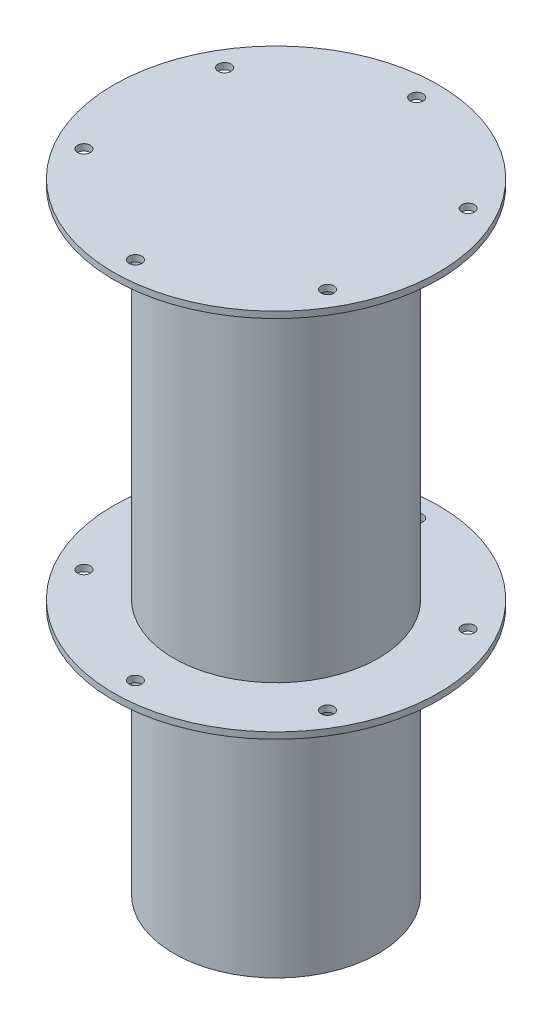
SolidWorks part; units mm, degrees
material "1060 Alloy"
ref_plane "Front Plane" through (0, 0, 0) normal (0, 0, 1) x (1, 0, 0)
ref_plane "Top Plane" through (0, 0, 0) normal (0, 1, 0) x (1, 0, 0)
ref_plane "Right Plane" through (0, 0, 0) normal (1, 0, 0) x (0, 0, -1)
sketch "Sketch1" plane through (0, 0, 0) normal (0, 0, 1) x (1, 0, 0)
  line L0 (0, -290.9908) -> (0, 411.7245) construction
  line L1 (-603.1552, 0) -> (651.163, 0) construction
  line L3 (101.6, 318.6092) -> (101.6, -36.9908)
  line L4 (101.6, -43.3408) -> (161.3582, -43.3408)
  line L5 (161.3582, -43.3408) -> (161.3582, -36.9908)
  line L6 (161.3582, -36.9908) -> (101.6, -36.9908)
  line L7 (101.6, -290.9908) -> (0, -290.9908)
  line L8 (101.6, -43.3408) -> (101.6, -290.9908)
  line L9 (0, 318.6092) -> (0, -290.9908)
  line L10 (101.6, 318.6092) -> (161.3582, 318.6092)
  line L11 (161.3582, 318.6092) -> (161.3582, 324.9592)
  line L12 (161.3582, 324.9592) -> (101.6, 324.9592)
  line L14 (101.6, 324.9592) -> (0, 324.9592)
  line L15 (0, 324.9592) -> (0, 318.6092)
  line L17 (0, -290.9908) -> (-0.9894, -290.842)
  dimension "D1" = 101.6
  dimension "D2" = 355.6
  dimension "D3" = 254
  dimension "D4" = 6.35
  dimension "D5" = 6.35
  dimension "D6" = 59.7582
  dimension "D7" = 59.7582
revolve "Revolve1" add sketch "Sketch1" angle 360 about L9
sketch "Sketch2" plane through (0, 324.9592, 0) normal (0, 1, 0) x (1, 0, 0)
  circle A0 centre (0, 0) radius 139.7
  circle A1 centre (0, 139.7) radius 6.35
  circle A2 centre (120.9837, 69.85) radius 6.35
  circle A3 centre (120.9837, -69.85) radius 6.35
  circle A4 centre (0, -139.7) radius 6.35
  circle A5 centre (-120.9837, -69.85) radius 6.35
  circle A6 centre (-120.9837, 69.85) radius 6.35
  point P18 (0, 0)
  dimension "D1" = 279.4
  dimension "D2" = 12.7
  dimension "D3" = 6
extrude "Cut-Extrude1" cut sketch "Sketch2" against normal through all contours A6 | A2 | A1 | A5 | A4 | A3
